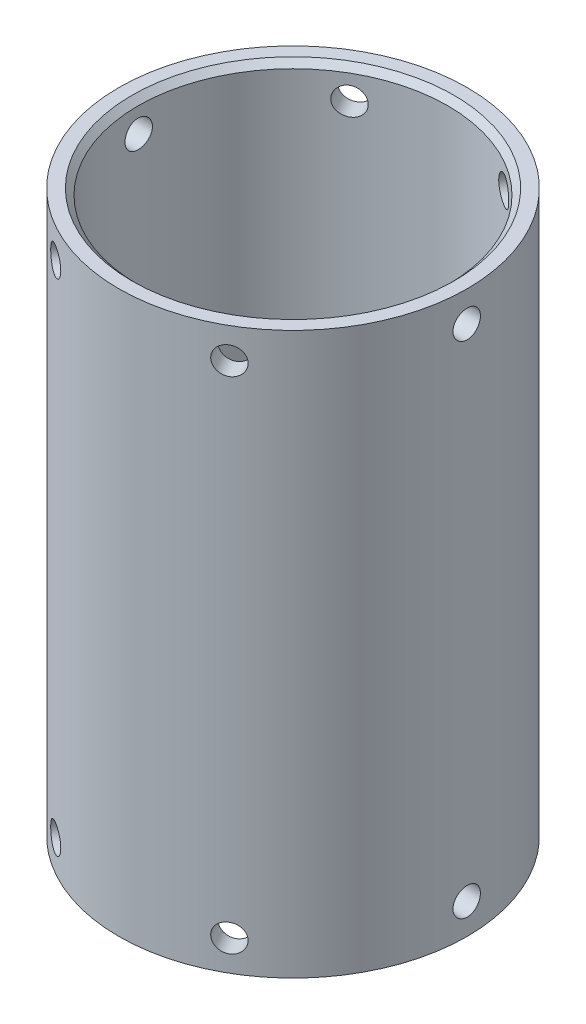
SolidWorks part; units mm, degrees
material "6061-T6 (SS)"
ref_plane "Front Plane" through (0, 0, 0) normal (0, 0, 1) x (1, 0, 0)
ref_plane "Top Plane" through (0, 0, 0) normal (0, 1, 0) x (1, 0, 0)
ref_plane "Right Plane" through (0, 0, 0) normal (1, 0, 0) x (0, 0, -1)
sketch "Sketch2" plane through (0, 0, 0) normal (0, 1, 0) x (1, 0, 0)
  circle A0 centre (0, 0) radius 28.575
  dimension "D1" = 57.15
extrude "Boss-Extrude1" add sketch "Sketch2" against normal blind 92
sketch "Sketch3" plane through (0, 0, 0) normal (0, 1, 0) x (1, 0, 0)
  circle A0 centre (0, 0) radius 25.4
  circle A1 centre (0, 0) radius 28.575 construction
  dimension "D1" = 3.175
extrude "Cut-Extrude1" cut sketch "Sketch3" against normal blind 110
sketch "Sketch7" plane through (0, 0, 0) normal (1, 0, 0) x (0, 0, -1)
  line L1 (25.4, 0) -> (-25.4, 0) construction
  line L5 (0, 0) -> (0, -29.1244) construction
  line L6 (0, 0) -> (44.9493, 0) construction
  line L7 (28.575, 0) -> (-28.575, 0) construction
  circle A1 centre (0, -5) radius 2.25
  dimension "D1" = 4.5
  dimension "D2" = 5
extrude "Cut-Extrude2" cut sketch "Sketch7" against normal blind 110
pattern_circular "CirPattern1" count 6 over 360 about axis through (0, 0, 0) along (0, -1, 0) of "Cut-Extrude2"
sketch "Sketch8" plane through (0, 0, 0) normal (1, 0, 0) x (0, 0, -1)
  line L0 (0, 0) -> (0, -29.1244) construction
  line L1 (25.4, 0) -> (-25.4, 0) construction
  line L3 (-28.575, -92) -> (28.575, -92) construction
  circle A0 centre (0, -10) radius 2.15
  circle A1 centre (0, -87) radius 2.25
  dimension "D1" = 4.3
  dimension "D2" = 10
  dimension "D4" = 4.5
  dimension "D3" = 5
extrude "Cut-Extrude5" cut sketch "Sketch8" against normal through all both and the other way through all contours A1
pattern_circular "CirPattern2" count 6 over 360 about axis through (0, 0, 0) along (0, -1, 0) of "Cut-Extrude5"
chamfer "Chamfer1" distance 1 angle 45 2 edges at (0, -92, 25.4) (0, 0, 25.4)
